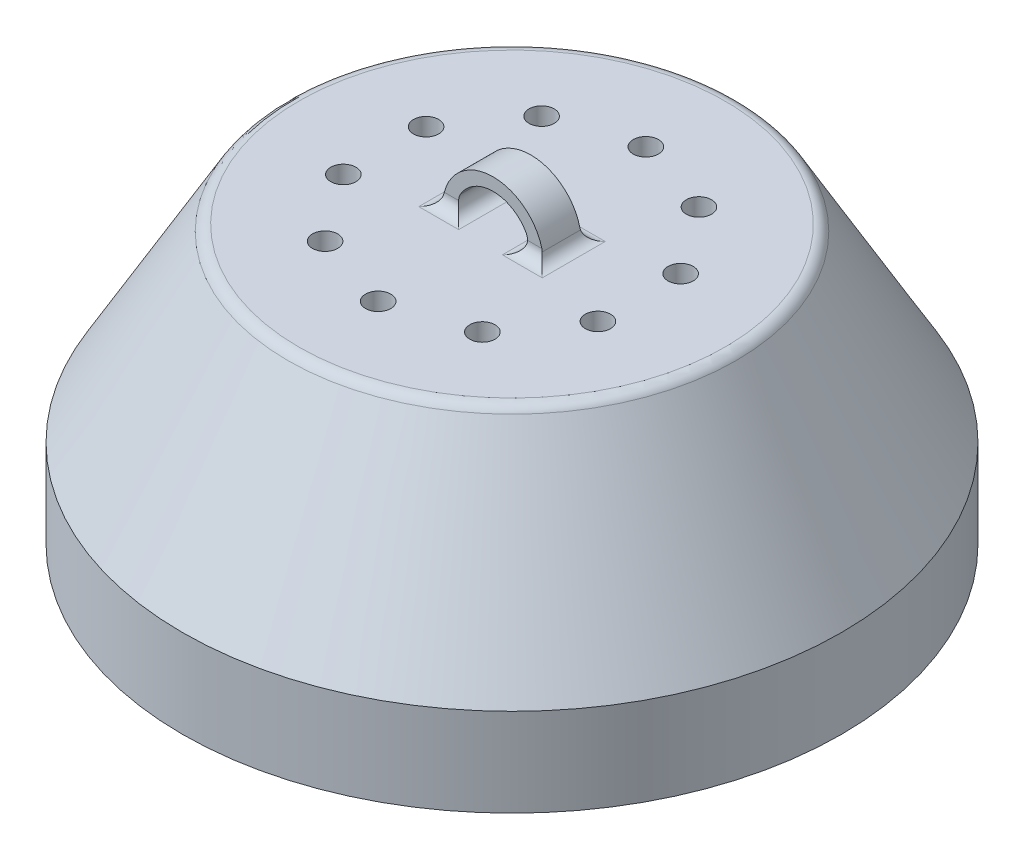
SolidWorks part; units mm, degrees
ref_plane "Front Plane" through (0, 0, 0) normal (0, 0, 1) x (1, 0, 0)
ref_plane "Top Plane" through (0, 0, 0) normal (0, 1, 0) x (1, 0, 0)
ref_plane "Right Plane" through (0, 0, 0) normal (1, 0, 0) x (0, 0, -1)
sketch "Sketch1" plane through (0, 0, 0) normal (0, 1, 0) x (1, 0, 0)
  circle A0 centre (0, 0) radius 24.75
  circle A1 centre (0, 0) radius 26.15
extrude "Boss-Extrude1" add sketch "Sketch1" along normal blind 7
sketch "Sketch3" plane through (0, 7, 0) normal (0, 1, 0) x (1, 0, 0)
  circle A0 centre (0, 0) radius 26.15
extrude "Boss-Extrude2" add sketch "Sketch3" along normal blind 15 draft 30
sketch "Sketch4" plane through (0, 7, 0) normal (0, -1, 0) x (1, 0, 0)
  circle A1 centre (0, 0) radius 24.75
extrude "Cut-Extrude1" cut sketch "Sketch4" against normal offset from surface 1.5 draft 30
sketch "Sketch5" plane through (0, 0, 0) normal (0, 0, 1) x (1, 0, 0)
  line L0 (17.4897, 22) -> (-17.4897, 22) construction
  line L1 (-4, 22) -> (-3, 22)
  line L2 (3, 22) -> (4, 22)
  arc A0 (4, 22) -> (-4, 22) centre (0, 22) ccw
  arc A1 (3, 22) -> (-3, 22) centre (0, 22) ccw
extrude "Boss-Extrude4" add sketch "Sketch5" along normal mid plane 3
fillet "Fillet2" radius 1 10 edges at (0, 22, 17.4897) (-4, 22, 0) (4, 22, 0) (-3.5, 22, -1.5) (3.5, 22, -1.5) (-3, 22, 0) (3, 22, 0) (-3.5, 22, 1.5) (3.5, 22, 1.5) (0, 0, 24.75)
sketch "Sketch6" plane through (0, 22, 0) normal (0, 1, 0) x (1, 0, 0)
  circle A0 centre (0, 10.6203) radius 1
  circle A1 centre (6.2425, 8.592) radius 1
  circle A2 centre (10.1005, 3.2819) radius 1
  circle A3 centre (10.1005, -3.2819) radius 1
  circle A4 centre (6.2425, -8.592) radius 1
  circle A5 centre (0, -10.6203) radius 1
  circle A6 centre (-6.2425, -8.592) radius 1
  circle A7 centre (-10.1005, -3.2819) radius 1
  circle A8 centre (-10.1005, 3.2819) radius 1
  circle A9 centre (-6.2425, 8.592) radius 1
  point P23 (0, 0)
  dimension "D1" = 10
extrude "Cut-Extrude2" cut sketch "Sketch6" against normal up to next
